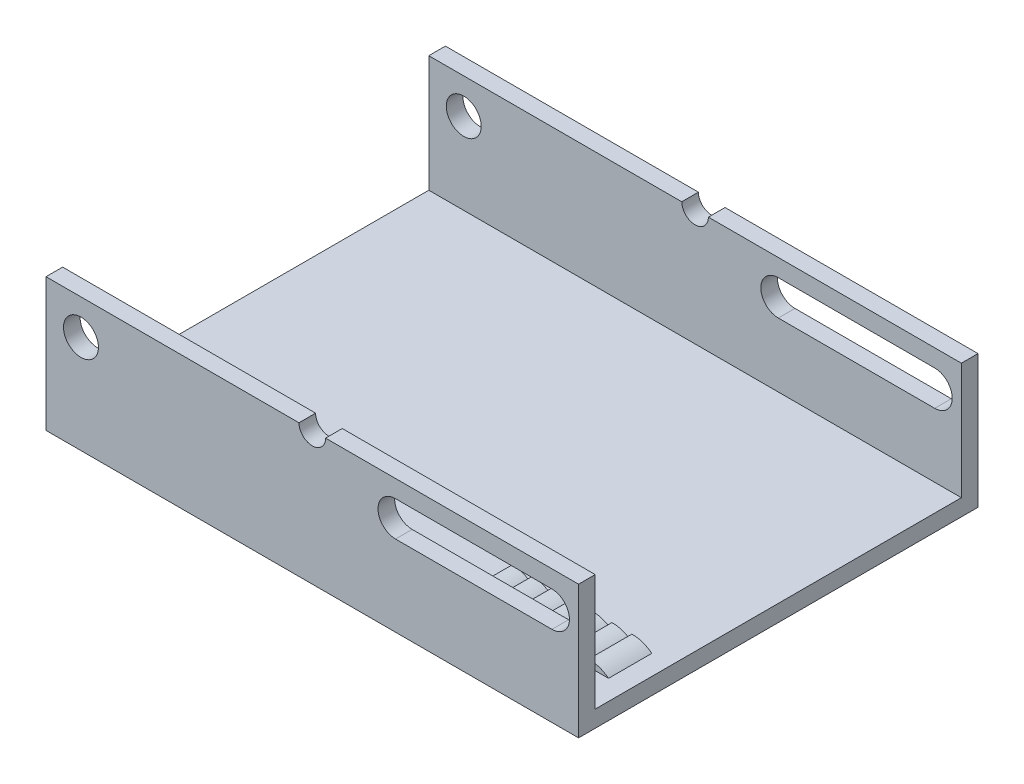
SolidWorks part; units mm, degrees
ref_plane "Vorne" through (0, 0, 0) normal (0, 0, 1) x (1, 0, 0)
ref_plane "Oben" through (0, 0, 0) normal (0, 1, 0) x (1, 0, 0)
ref_plane "Seite" through (0, 0, 0) normal (1, 0, 0) x (0, 0, -1)
sketch "Skizze9" plane through (0, 0, 0) normal (1, 0, 0) x (0, 0, -1)
  line L0 (-60, 40) -> (-60, 0)
  line L1 (-60, 0) -> (60, 0)
  line L2 (60, 0) -> (60, 40)
  line L3 (60, 40) -> (55, 40)
  line L4 (55, 40) -> (55, 5)
  line L5 (55, 5) -> (-55, 5)
  line L6 (-55, 5) -> (-55, 40)
  line L7 (-55, 40) -> (-60, 40)
  line L8 (0, 0) -> (0, 5) construction
  dimension "B" = 120
  dimension "D2" = 5
  dimension "D3" = 40
extrude "Aufsatz-Linear austragen3" add sketch "Skizze9" along normal mid plane 160
sketch "Skizze10" plane through (0, 0, 60) normal (0, 0, 1) x (1, 0, 0)
  line L0 (25, 34.75) -> (72, 34.75)
  line L2 (72, 24.25) -> (25, 24.25)
  line L4 (-80, 40) -> (-80, 0) construction
  line L5 (80, 40) -> (-80, 40) construction
  line L6 (80, 40) -> (80, 0) construction
  circle A0 centre (-69.5, 29.5) radius 5.25
  arc A1 (25, 34.75) -> (25, 24.25) centre (25, 29.5) ccw
  arc A2 (72, 24.25) -> (72, 34.75) centre (72, 29.5) ccw
  dimension "D2" = 10.5
  dimension "D1" = 10.5
  dimension "D3" = 10.5
  dimension "D4" = 8
  dimension "D5" = 47
extrude "Schnitt-Linear austragen1" cut sketch "Skizze10" against normal through all both and the other way through all
sketch "Skizze12" plane through (0, 0, 0) normal (0, 0, 1) x (1, 0, 0)
  line L0 (80, 40) -> (-80, 40) construction
  line L1 (-4, 40) -> (4, 40)
  arc A0 (-4, 40) -> (4, 40) centre (0, 40) ccw
  dimension "D1" = 4
extrude "Schnitt-Linear austragen2" cut sketch "Skizze12" against normal through all both and the other way through all
sketch "Skizze18" plane through (0, 0, 0) normal (0, 0, -1) x (-1, 0, 0)
  line L1 (-32, 5) -> (-38, 5)
  line L37 (-32, 7) -> (-32, 5)
  line L42 (-80, 5) -> (80, 5) construction
  line L44 (-38, 5) -> (-44, 5) [skipped]
  line L47 (-44, 5) -> (-50, 5) [skipped]
  line L48 (-50, 5) -> (-56, 5) [skipped]
  line L50 (-56, 5) -> (-62, 5) [skipped]
  line L52 (-68, 5) -> (-74, 5) [skipped]
  line L53 (-62, 5) -> (-68, 5) [skipped]
  line L56 (-74, 5) -> (-80, 5) [skipped]
  line L58 (-80, 5) -> (-86, 5) [skipped]
  line L60 (-86, 5) -> (-92, 5) [skipped]
  line L63 (-92, 5) -> (-98, 5) [skipped]
  line L64 (-98, 5) -> (-104, 5) [skipped]
  arc A0 (-25, 24.25) -> (-25, 34.75) centre (-25, 29.5) ccw construction
  spline S0 degree 2 poles (-38, 5) (-35.1677, 7.1247) (-32, 7) knots 0 0 0 0.477298 0.477298 0.477298
  dimension "D2" = 2
  dimension "D3" = 7
  dimension "D4" = 12
  dimension "D5" = 6
extrude "Aufsatz-Linear austragen4" add sketch "Skizze18" along direction (0, 0, 1) on the side against the normal blind 45
pattern_linear "Lineares Muster1" count 7 spacing 6 along (-1, 0, 0) of "Aufsatz-Linear austragen4"
sketch "Skizze19" plane through (0, 0, 0) normal (0, 0, 1) x (1, 0, 0)
  line L0 (-80, 40) -> (-80, 0) construction
  line L1 (80, 40) -> (-80, 40)
  line L2 (80, 40) -> (80, 5)
  line L3 (80, 5) -> (-80, 5)
  line L4 (-80, 40) -> (-80, 5)
  line L5 (0, 5) -> (0, 40) construction
  line L6 (80, 22.5) -> (-80, 22.5) construction
  line L7 (80, 5) -> (-80, 5) construction
  point P660 (0, 22.5)
extrude "Schnitt-Linear austragen3" cut sketch "Skizze19" along normal blind 32
equation "\"Basis_Breite\"= 120"
equation "\"B@Skizze9\"= \"Basis_Breite\""
equation "\"D3@Skizze9\" = \"Basis_höhe\"'Höhe"
equation "\"Basis_höhe\" = 40"
equation "\"Basis_Dicke\"= 5"
equation "\"D2@Skizze9\"= \"Basis_Dicke\""
equation "\"Loch\"= 10.5"
equation "\"D2@Skizze10\"= \"Loch\""
equation "\"D1@Skizze10\"= \"Loch\""
equation "\"D3@Skizze10\"= \"Loch\""
